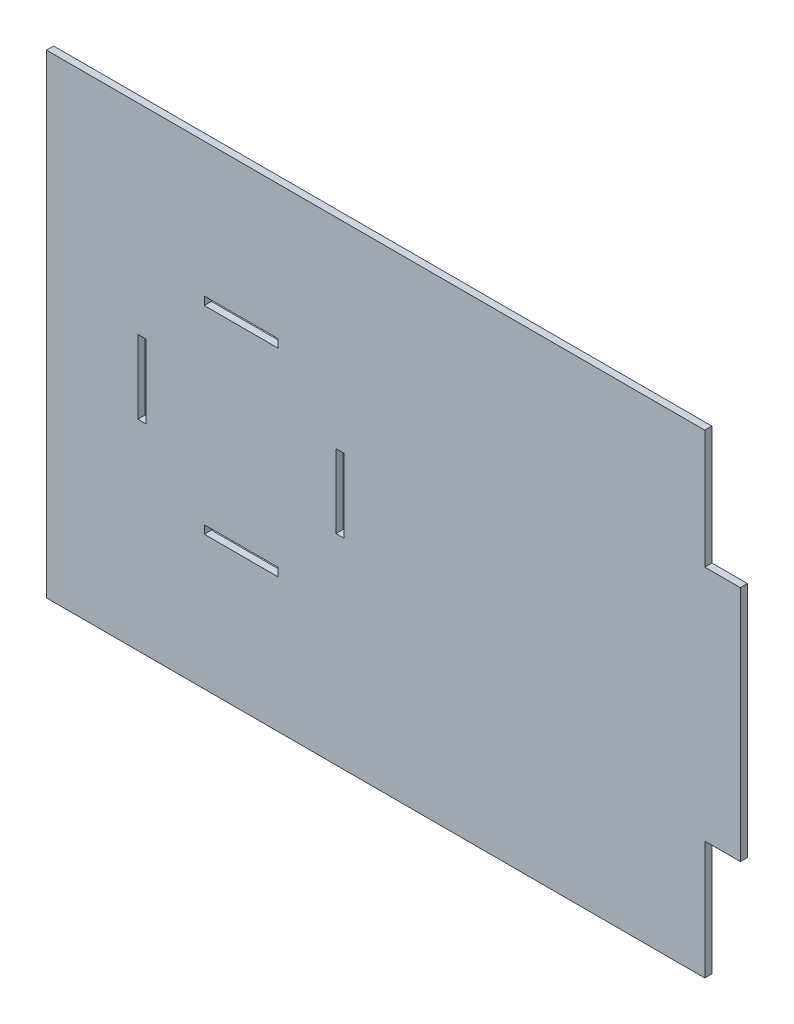
SolidWorks part; units mm, degrees
ref_plane "Plano frontal" through (0, 0, 0) normal (0, 0, 1) x (1, 0, 0)
ref_plane "Plano superior" through (0, 0, 0) normal (0, 1, 0) x (1, 0, 0)
ref_plane "Plano direito" through (0, 0, 0) normal (1, 0, 0) x (0, 0, -1)
sketch "Esboço1" plane through (0, 0, 0) normal (0, 0, 1) x (1, 0, 0)
  line L1 (-277.5, -100) -> (277.5, -100)
  line L2 (-277.5, -100) -> (-277.5, 100)
  line L3 (-277.5, 100) -> (277.5, 100)
  line L4 (277.5, -100) -> (277.5, 100)
  line L5 (-277.5, -100) -> (277.5, 100) construction
  line L6 (-277.5, 100) -> (277.5, -100) construction
  point P0 (0, 0)
  dimension "D1" = 555
  dimension "D2" = 200
extrude "Ressalto-extrusão1" add sketch "Esboço1" along normal blind 3
sketch "Esboço2" plane through (0, 0, 3) normal (0, 0, 1) x (1, 0, 0)
  line L0 (-277.5, 0) -> (277.5, 0) construction
  line L1 (-277.5, 100) -> (-277.5, -100) construction
  line L2 (277.5, -100) -> (277.5, 100) construction
  line L3 (0, 100) -> (0, -100) construction
  line L4 (277.5, 100) -> (-277.5, 100) construction
  line L5 (-277.5, -100) -> (277.5, -100) construction
  line L6 (-195.5, 100) -> (-195.5, -100) construction
  line L11 (239, 15.5) -> (235.5, 15.5)
  line L12 (235.5, -15.5) -> (235.5, 15.5)
  line L13 (-155.5, -15.5) -> (-152, -15.5)
  line L14 (-155.5, -15.5) -> (-155.5, 15.5)
  line L15 (-155.5, 15.5) -> (-152, 15.5)
  line L16 (-152, -15.5) -> (-152, 15.5)
  line L17 (-155.5, -15.5) -> (-152, 15.5) construction
  line L18 (-155.5, 15.5) -> (-152, -15.5) construction
  line L19 (-239, -15.5) -> (-235.5, -15.5)
  line L20 (-239, -15.5) -> (-239, 15.5)
  line L21 (-239, 15.5) -> (-235.5, 15.5)
  line L22 (-235.5, -15.5) -> (-235.5, 15.5)
  line L23 (-239, -15.5) -> (-235.5, 15.5) construction
  line L24 (-239, 15.5) -> (-235.5, -15.5) construction
  line L25 (-211, 40) -> (-180, 40)
  line L26 (-211, -43.5) -> (-180, -43.5)
  line L27 (-211, -43.5) -> (-211, -40)
  line L28 (-211, -40) -> (-180, -40)
  line L29 (-180, -43.5) -> (-180, -40)
  line L30 (-211, -43.5) -> (-180, -40) construction
  line L31 (-211, -40) -> (-180, -43.5) construction
  line L32 (-180, 43.5) -> (-180, 40)
  line L33 (-211, 43.5) -> (-180, 43.5)
  line L34 (-211, 43.5) -> (-211, 40)
  line L35 (239, -15.5) -> (235.5, -15.5)
  line L36 (239, -15.5) -> (239, 15.5)
  line L37 (155.5, 15.5) -> (152, 15.5)
  line L38 (152, -15.5) -> (152, 15.5)
  line L39 (155.5, -15.5) -> (152, -15.5)
  line L40 (155.5, -15.5) -> (155.5, 15.5)
  line L41 (211, -40) -> (180, -40)
  line L42 (180, -43.5) -> (180, -40)
  line L43 (211, -43.5) -> (180, -43.5)
  line L44 (211, -43.5) -> (211, -40)
  line L45 (211, 43.5) -> (211, 40)
  line L46 (211, 43.5) -> (180, 43.5)
  line L47 (180, 43.5) -> (180, 40)
  line L48 (211, 40) -> (180, 40)
  point P17 (-153.75, 0)
  point P22 (-237.25, 0)
  point P29 (-195.5, -41.75)
  dimension "D3" = 3.5
  dimension "D4" = 31
  dimension "D6" = 122
  dimension "D7" = 31
  dimension "D8" = 3.5
  dimension "D9" = 80
  dimension "D10" = 31
  dimension "D11" = 3.5
  dimension "D12" = 80
  dimension "D13" = 40
extrude "Corte-extrusão1" cut sketch "Esboço2" against normal through all
sketch "Esboço3" plane through (0, 0, 3) normal (0, 0, 1) x (1, 0, 0)
  line L0 (0, 100) -> (0, 50)
  line L1 (277.5, 100) -> (-277.5, 100) construction
  line L2 (-277.5, -100) -> (277.5, -100) construction
  line L3 (0, -50) -> (15, -50)
  line L4 (15, -50) -> (15, 50)
  line L5 (15, 50) -> (0, 50)
  line L6 (0, -50) -> (0, -100)
  line L11 (277.5, -100) -> (277.5, 100)
  line L12 (277.5, 100) -> (-277.5, 100)
  line L13 (-277.5, 100) -> (-277.5, -100)
  line L14 (-277.5, -100) -> (277.5, -100)
  line L15 (277.5, -100) -> (277.5, 100)
  line L16 (277.5, 100) -> (0, 100)
  line L18 (0, -100) -> (277.5, -100)
  dimension "D1" = 100
  dimension "D2" = 15
  dimension "D3" = 50
  dimension "D4" = 0
extrude "Corte-extrusão2" cut sketch "Esboço3" against normal through all
